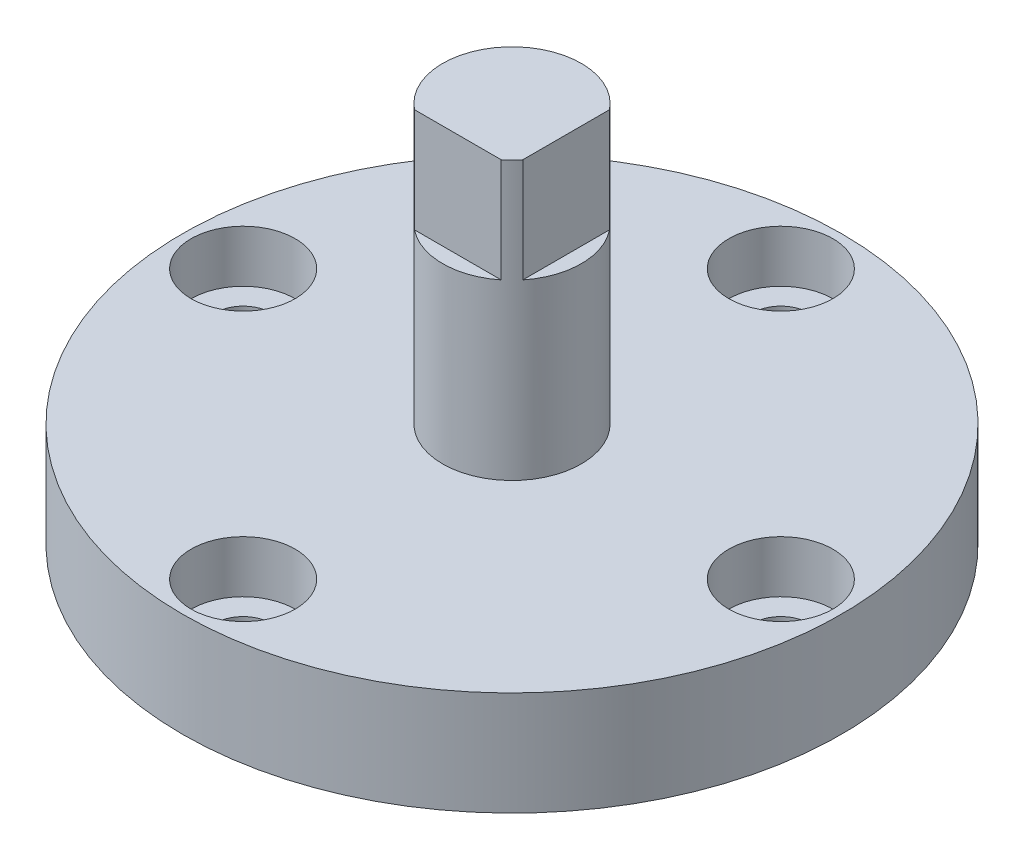
SolidWorks part; units mm, degrees
ref_plane "Front Plane" through (0, 0, 0) normal (0, 0, 1) x (1, 0, 0)
ref_plane "Top Plane" through (0, 0, 0) normal (0, 1, 0) x (1, 0, 0)
ref_plane "Right Plane" through (0, 0, 0) normal (1, 0, 0) x (0, 0, -1)
sketch "Sketch1" plane through (0, 0, 0) normal (0, 1, 0) x (1, 0, 0)
  circle A0 centre (0, 0) radius 19
  circle A1 centre (0, 15.5) radius 3
  circle A2 centre (15.5, 0) radius 3
  circle A3 centre (0, -15.5) radius 3
  circle A4 centre (-15.5, 0) radius 3
  point P14 (0, 0)
  dimension "D1" = 38
  dimension "D2" = 6
  dimension "D3" = 15.5
  dimension "D4" = 4
extrude "Boss-Extrude1" add sketch "Sketch1" along normal blind 3
sketch "Sketch2" plane through (0, 3, 0) normal (0, 1, 0) x (1, 0, 0)
  circle A0 centre (0, 0) radius 4
  dimension "D1" = 8
extrude "Boss-Extrude2" add sketch "Sketch2" along normal blind 16
sketch "Sketch4" plane through (0, 19, 0) normal (0, 1, 0) x (1, 0, 0)
  line L0 (-2.5, -3.1225) -> (2.5, -3.1225)
  line L1 (3.1225, 2.5) -> (3.1225, -2.5)
  circle A0 centre (0, 0) radius 4 construction
  arc A1 (-2.5, -3.1225) -> (2.5, -3.1225) centre (0, 0) ccw
  arc A2 (3.1225, -2.5) -> (3.1225, 2.5) centre (0, 0) ccw
  circle A3 centre (0, 0) radius 4 construction
  point P12 (0, -3.1225)
  dimension "D1" = 5
  dimension "D2" = 5
extrude "Cut-Extrude1" cut sketch "Sketch4" against normal blind 6
sketch "Sketch5" plane through (0, 0, 0) normal (0, -1, 0) x (1, 0, 0)
  circle A0 centre (0, 0) radius 19
  circle A1 centre (0, 15.5) radius 1.6
  circle A2 centre (-15.5, 0) radius 1.6
  circle A3 centre (0, -15.5) radius 1.6
  circle A4 centre (15.5, 0) radius 1.6
  dimension "D1" = 3.2
extrude "Boss-Extrude3" add sketch "Sketch5" along normal blind 3
